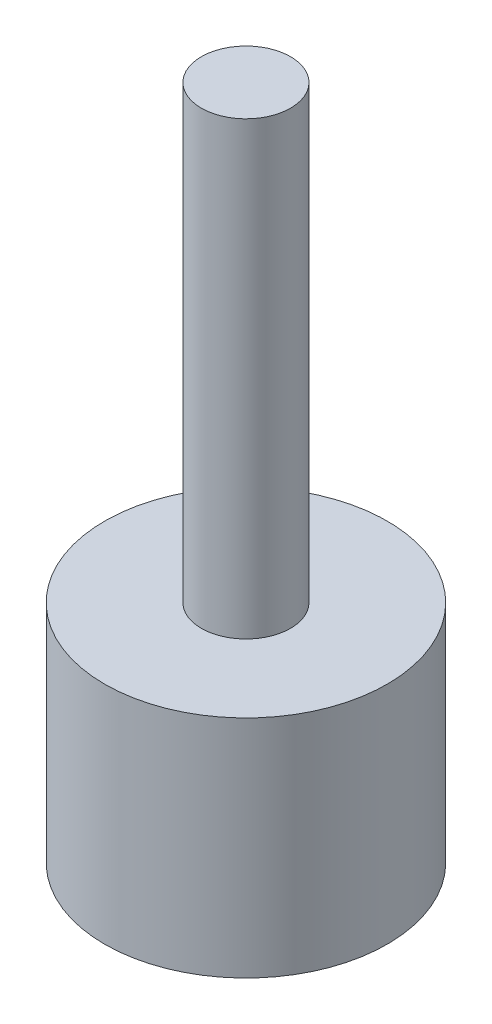
SolidWorks part; units mm, degrees
ref_plane "Front Plane" through (0, 0, 0) normal (0, 0, 1) x (1, 0, 0)
ref_plane "Top Plane" through (0, 0, 0) normal (0, 1, 0) x (1, 0, 0)
ref_plane "Right Plane" through (0, 0, 0) normal (1, 0, 0) x (0, 0, -1)
sketch "Sketch1" plane through (0, 0, 0) normal (0, 1, 0) x (1, 0, 0)
  line L0 (-1.4861, 1.3534) -> (1.4861, 1.3534)
  line L1 (-1.4918, -1.3471) -> (1.4918, -1.3471)
  circle A0 centre (0, 0) radius 2.01
  circle A1 centre (0, 0) radius 3.1359
extrude "Boss-Extrude1" add sketch "Sketch1" along normal blind 5 contours A1 A0 | L1 A0 L0 | L0 A0 | L1 A0
sketch "Sketch2" plane through (0, 0, 0) normal (0, 1, 0) x (1, 0, 0)
  line L0 (1.9958, -1.5873) -> (-1.9958, -1.5873)
  line L1 (-1.9958, 1.5873) -> (1.9958, 1.5873)
  circle A0 centre (0, 0) radius 2.55
  circle A1 centre (0, 0) radius 3.1359
extrude "Cut-Extrude4" cut sketch "Sketch2" along normal blind 4 contours L0 A0 L1
sketch "Sketch4" plane through (0, 5, 0) normal (0, 1, 0) x (1, 0, 0)
  circle A0 centre (0, 0) radius 0.99
extrude "Boss-Extrude3" add sketch "Sketch4" along normal blind 10
